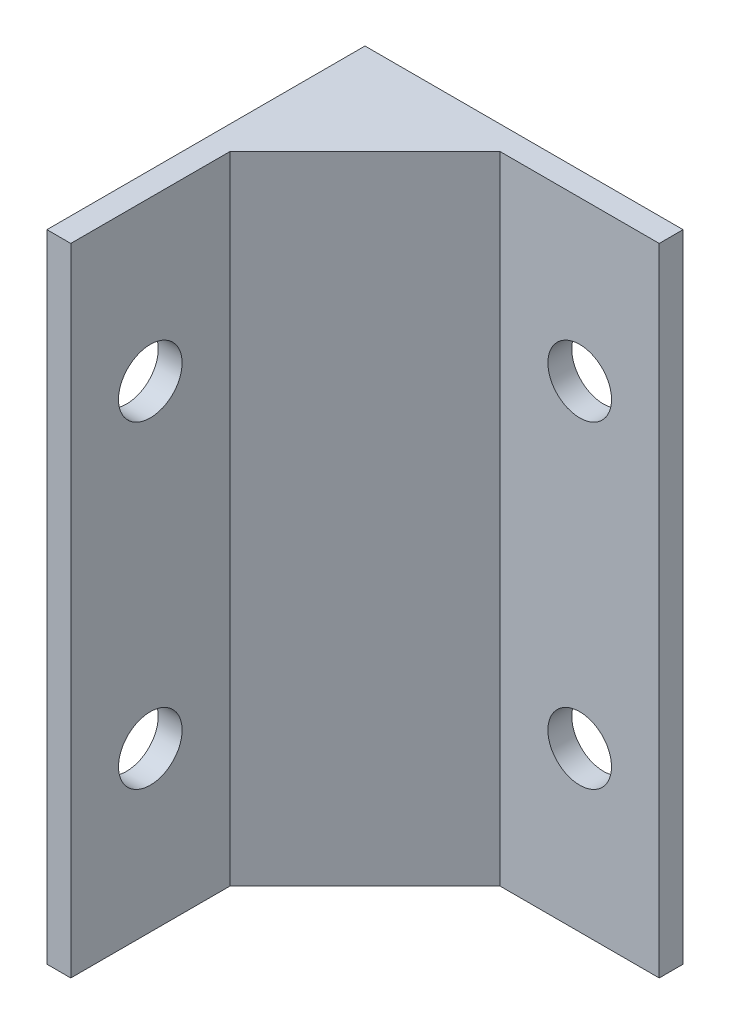
SolidWorks part; units mm, degrees
ref_plane "Płaszczyzna przednia" through (0, 0, 0) normal (0, 0, 1) x (1, 0, 0)
ref_plane "Płaszczyzna górna" through (0, 0, 0) normal (0, 1, 0) x (1, 0, 0)
ref_plane "Płaszczyzna prawa" through (0, 0, 0) normal (1, 0, 0) x (0, 0, -1)
sketch "Szkic1" plane through (0, 0, 0) normal (0, 1, 0) x (1, 0, 0)
  line L1 (-20, -20) -> (20, -20)
  line L2 (-20, -20) -> (-20, 20)
  line L3 (-20, 20) -> (20, 20)
  line L4 (20, -20) -> (20, 20)
  line L5 (-20, -20) -> (20, 20) construction
  line L6 (-20, 20) -> (20, -20) construction
  point P0 (0, 0)
  dimension "D1" = 40
  dimension "D2" = 40
extrude "Dodanie-wyciągnięcie1" add sketch "Szkic1" along normal blind 80
sketch "Szkic2" plane through (0, 80, 0) normal (0, 1, 0) x (1, 0, 0)
  line L0 (-17, -20) -> (-17, 0)
  line L1 (-20, -20) -> (20, -20) construction
  line L2 (-17, 0) -> (0, 17)
  line L3 (0, 17) -> (20, 17)
  line L4 (20, -20) -> (20, 20) construction
  line L5 (20, 20) -> (-20, 20) construction
  line L6 (-20, 20) -> (-20, -20) construction
  point P12 (0, 0)
  point P14 (0, 0)
  line M4 (20, -20) -> (20, 20)
  line M7 (-20, -20) -> (20, -20)
  dimension "D1" = 3
  dimension "D2" = 3
extrude "Wytnij-wyciągnięcie2" cut sketch "Szkic2" against normal blind 80 and the other way through all contours L3 L2 L0 M7 M4
sketch "Szkic3" plane through (0, 0, -17) normal (0, 0, 1) x (1, 0, 0)
  line L0 (0, 0) -> (20, 0) construction
  line L1 (20, 40) -> (-34.4737, 40) construction
  line L2 (20, 80) -> (20, 0) construction
  circle A0 centre (10, 60) radius 4
  circle A2 centre (10, 20) radius 4
  point P2 (0, 0)
  point P4 (0, 0)
  point P7 (10, 0)
  dimension "D2" = 8
  dimension "D3" = 40
extrude "Wytnij-wyciągnięcie3" cut sketch "Szkic3" against normal through all
ref_plane "Płaszczyzna1" through (0, 0, 0) normal (-0.7071, 0, 0.7071) x (0.7071, 0, 0.7071)
mirror "Lustro1" about plane through (0, 0, 0) normal (-0.7071, 0, 0.7071) of "Wytnij-wyciągnięcie3"
